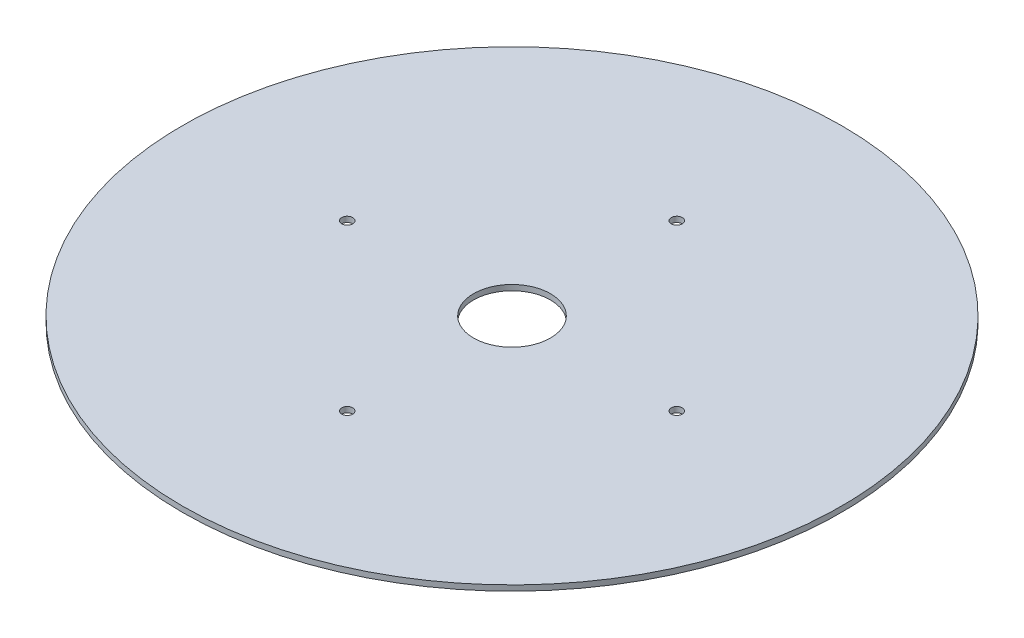
SolidWorks part; units mm, degrees
material "ABS PC"
ref_plane "Front Plane" through (0, 0, 0) normal (0, 0, 1) x (1, 0, 0)
ref_plane "Top Plane" through (0, 0, 0) normal (0, 1, 0) x (1, 0, 0)
ref_plane "Right Plane" through (0, 0, 0) normal (1, 0, 0) x (0, 0, -1)
sketch "Sketch3" plane through (0, 0, 0) normal (0, 1, 0) x (1, 0, 0)
  line L0 (0, 188.4398) -> (0, -197.2693) construction
  line L1 (-221.2019, 0) -> (249.5492, 0) construction
  circle A0 centre (0, 0) radius 150
  circle A1 centre (0, 0) radius 17.5
  circle A2 centre (-75, 0) radius 2.5
  circle A4 centre (0, 75) radius 2.5
  circle A5 centre (75, 0) radius 2.5
  circle A6 centre (0, -75) radius 2.5
  point P21 (0, 0)
  dimension "D1" = 300
  dimension "D2" = 35
  dimension "D3" = 5
  dimension "D5" = 75
  dimension "D7" = 4
extrude "Boss-Extrude1" add sketch "Sketch3" along normal blind 2.5
